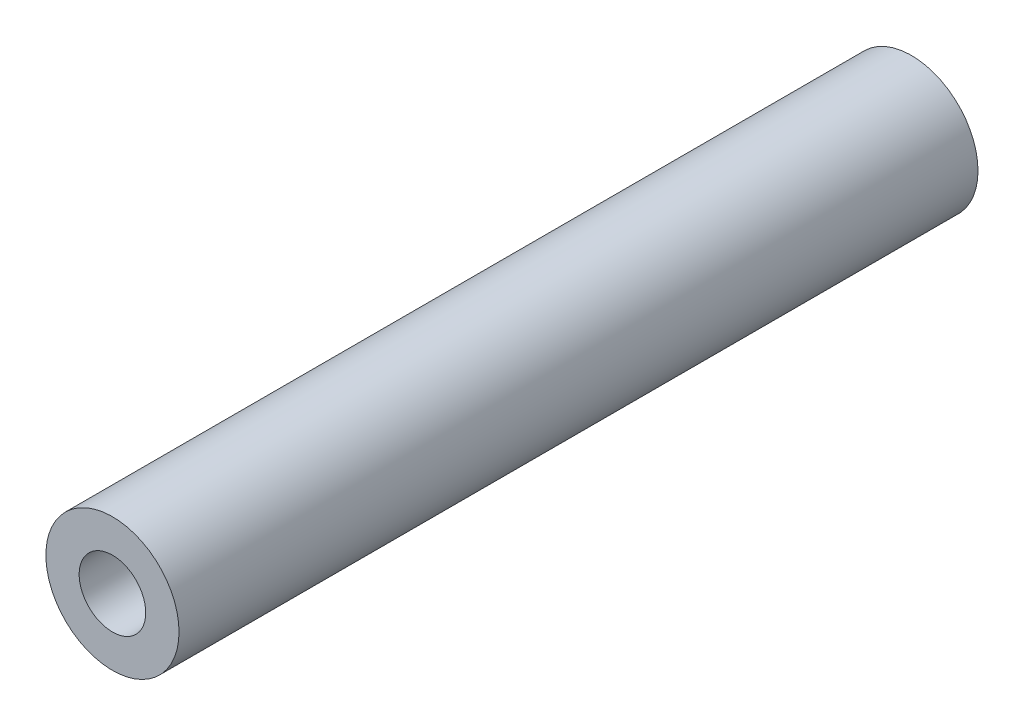
SolidWorks part; units mm, degrees
ref_plane "前视基准面" through (0, 0, 0) normal (0, 0, 1) x (1, 0, 0)
ref_plane "上视基准面" through (0, 0, 0) normal (0, 1, 0) x (1, 0, 0)
ref_plane "右视基准面" through (0, 0, 0) normal (1, 0, 0) x (0, 0, -1)
sketch "草图1" plane through (0, 0, 0) normal (0, 0, 1) x (1, 0, 0)
  circle A0 centre (0, 0) radius 5
  circle A1 centre (0, 0) radius 2.5
  dimension "D1" = 5
  dimension "D2" = 10
extrude "凸台-拉伸1" add sketch "草图1" along normal blind 60
